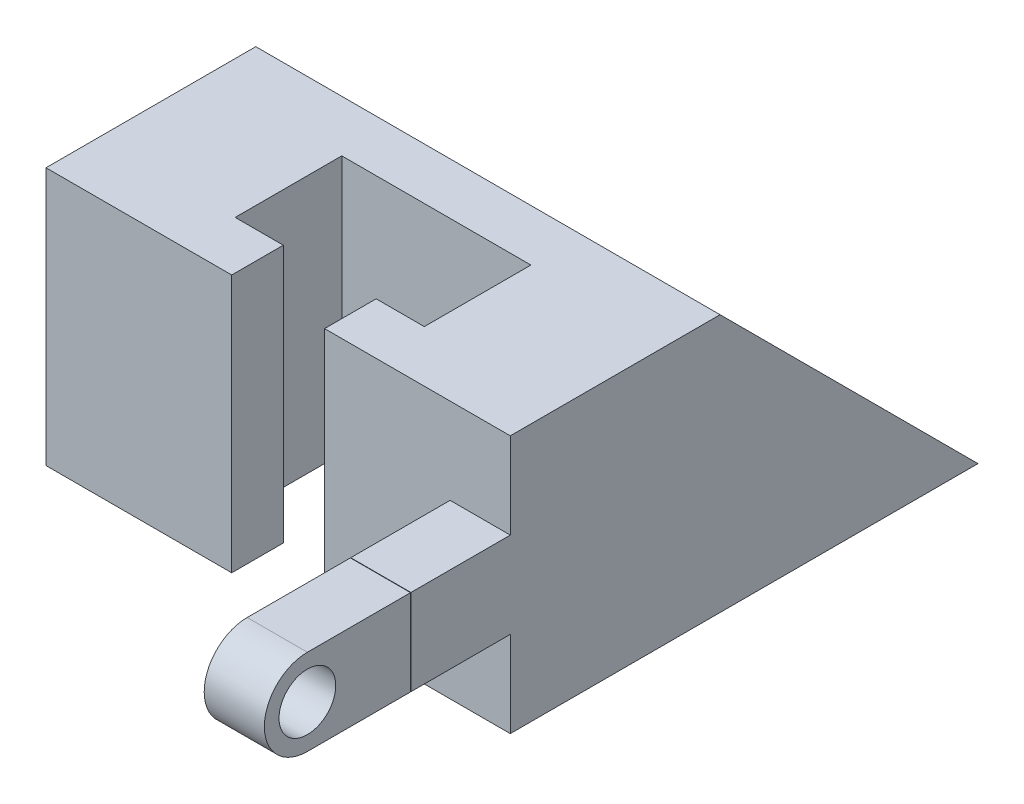
SolidWorks part; units mm, degrees
ref_plane "前视基准面" through (0, 0, 0) normal (0, 0, 1) x (1, 0, 0)
ref_plane "上视基准面" through (0, 0, 0) normal (0, 1, 0) x (1, 0, 0)
ref_plane "右视基准面" through (0, 0, 0) normal (1, 0, 0) x (0, 0, -1)
sketch "草图1" plane through (0, 0, 0) normal (0, 1, 0) x (1, 0, 0)
  line L0 (-5.5, 0) -> (5.5, 0)
  line L1 (5.5, 0) -> (5.5, -6.2)
  line L2 (5.5, -6.2) -> (2.7, -6.2)
  line L3 (2.7, -6.2) -> (2.7, -9.2)
  line L4 (2.7, -9.2) -> (5.5, -9.2)
  line L5 (5.5, -9.2) -> (5.5, -17)
  line L6 (5.5, -17) -> (8.5, -17)
  line L8 (-8.5, 3) -> (8.5, 3)
  line L9 (8.5, 3) -> (8.5, -17)
  line L10 (-5.5, -17) -> (-8.5, -17)
  line L11 (-5.5, -9.2) -> (-5.5, -17)
  line L12 (-2.7, -9.2) -> (-5.5, -9.2)
  line L13 (-2.7, -6.2) -> (-2.7, -9.2)
  line L14 (-5.5, -6.2) -> (-2.7, -6.2)
  line L15 (-5.5, 0) -> (-5.5, -6.2)
  line L16 (-8.5, 3) -> (-8.5, -17)
extrude "凸台-拉伸2" add sketch "草图1" along normal blind 15
sketch "草图2" plane through (8.5, 0, 0) normal (1, 0, 0) x (0, 0, -1)
  line L0 (-17, 15) -> (-17, 10)
  line L1 (-17, 15) -> (-17, 0) construction
  line L2 (-17, 0) -> (-17, 5)
  line L3 (-17, 15) -> (-9.2, 15)
  line L4 (-17, 15) -> (3, 15) construction
  line L5 (-9.2, 15) -> (-9.2, 10)
  line L6 (-9.2, 10) -> (-17, 10)
  line L7 (-17, 5) -> (-9.2, 5)
  line L8 (-9.2, 5) -> (-9.2, 0)
  line L9 (-17, 0) -> (3, 0) construction
  line L10 (-9.2, 0) -> (-17, 0)
extrude "切除-拉伸1" cut sketch "草图2" against normal blind 23
sketch "草图3" plane through (-8.5, 0, 0) normal (-1, 0, 0) x (0, 0, 1)
  line L0 (-3, 15) -> (-3, 7.5)
  line L1 (-3, 15) -> (-3, 0) construction
  line L2 (-3, 7.5) -> (15, 7.5)
  circle A0 centre (15, 7.5) radius 1.65
extrude "切除-拉伸2" cut sketch "草图3" against normal blind 23
sketch "草图4" plane through (0, 0, 17) normal (0, 0, 1) x (1, 0, 0)
  line L0 (-8.5, 10) -> (-5.5, 10)
  line L1 (-8.5, 10) -> (-8.5, 5.005)
  line L2 (-5.5, 10) -> (-5.5, 5.005)
  line L3 (-8.5, 5.005) -> (-5.5, 5.005)
  line L4 (-5.5, 10) -> (-5.5, 5) construction
  line L5 (-8.5, 10) -> (-5.5, 10) construction
  line L6 (5.5, 10) -> (8.5, 10)
  line L7 (5.5, 10) -> (5.5, 4.9814)
  line L8 (8.5, 10) -> (8.5, 4.9814)
  line L9 (5.5, 4.9814) -> (8.5, 4.9814)
extrude "凸台-拉伸3" add sketch "草图4" along normal blind 0.5
sketch "草图5" plane through (-8.5, 0, 0) normal (-1, 0, 0) x (0, 0, 1)
  line L0 (15, 10) -> (17.5, 10)
  line L1 (17.5, 10) -> (17.5, 7.5)
  line L2 (17.5, 7.5) -> (17.5, 5.005)
  line L3 (17.5, 5.005) -> (15, 5)
  line L4 (17.5, 5.005) -> (17.7329, 2.2884)
  line L5 (17.7329, 2.2884) -> (15, 5)
  circle A0 centre (15, 7.5) radius 2.5
extrude "切除-拉伸4" cut sketch "草图5" against normal blind 20.5
sketch "草图7" plane through (-8.5, 0, 0) normal (-1, 0, 0) x (0, 0, 1)
  line L0 (-3, 15) -> (-3, 0)
  line L1 (-3, 0) -> (-18, 0)
  line L2 (-18, 0) -> (-3, 15)
extrude "凸台-拉伸4" add sketch "草图7" against normal blind 17
sketch "草图8" plane through (0, 15, 0) normal (0, 1, 0) x (1, 0, 0)
  line L0 (-8.5, 3) -> (-8.5, 5)
  line L1 (-8.5, 3) -> (-8.5, 18) construction
  line L2 (-8.5, 5) -> (-6.5, 5)
  line L3 (-6.5, 5) -> (-6.5, 18)
  line L4 (-6.5, 5) -> (8.5, 5)
  line L5 (8.5, 3) -> (8.5, 18) construction
  line L6 (8.5, 5) -> (6.5, 5)
  line L7 (6.5, 5) -> (6.5, 18)
  line L8 (6.5, 18) -> (-6.5, 18)
extrude "切除-拉伸5" cut sketch "草图8" against normal blind 14 contours L7 L8 L3 L4
sketch "草图9" plane through (0, 1, 0) normal (0, 1, 0) x (1, 0, 0)
  line L0 (0, 5) -> (0, 8)
  line L1 (-6.5, 5) -> (6.5, 5) construction
  line L2 (0, 8) -> (-4, 8)
  circle A0 centre (-4, 8) radius 1.65
  circle A1 centre (4, 8) radius 1.65
  circle A2 centre (-4, 14) radius 1.65
  circle A3 centre (4, 14) radius 1.65
  dimension "D1" = 2
extrude "切除-拉伸6" cut sketch "草图9" against normal blind 14
sketch "草图10" plane through (-8.5, 0, 0) normal (-1, 0, 0) x (0, 0, 1)
  line L0 (15, 10) -> (25, 10)
  line L2 (15, 5) -> (25, 5)
  line L3 (25, 5) -> (25, 10)
  line L4 (15, 10) -> (15, 5)
  circle A0 centre (25, 7.5) radius 2.5
  circle A1 centre (25, 7.5) radius 1.65
  circle M1 centre (15, 7.5) radius 1.65
  arc M3 (15, 5) -> (15, 10) centre (15, 7.5) ccw
extrude "凸台-拉伸8" add sketch "草图10" along normal mid plane 50 contours A1 L3 A0 | A1 L3 A0 | A0 L0 L2 M3 | L4 M3 M1 | L4 M1 | L4 M1
sketch "草图11" plane through (0, 10, 0) normal (0, 1, 0) x (1, 0, 0)
  line L0 (-8.5, -15) -> (-16.5, -15)
  line L1 (-33.5, -15) -> (-8.5, -15) construction
  line L2 (-8.5, -15) -> (-8.5, -35.0128)
  line L3 (-8.5, -15) -> (-16.7588, -15)
  line L4 (-8.5, -35.0128) -> (-16.7588, -35.0128)
  line L5 (-16.7588, -15) -> (-16.7588, -35.0128)
  line L6 (-16.7588, -35.0128) -> (-38.7573, -35.0128)
  line L7 (-16.7588, -35.0128) -> (-16.7588, 0.8187)
  line L8 (-38.7573, -35.0128) -> (-38.7573, 0.8187)
  line L9 (-16.7588, 0.8187) -> (-38.7573, 0.8187)
  line M3 (-8.5, -15) -> (-33.5, -15)
  line M4 (-33.5, -15) -> (-33.5, -25)
  line M5 (-33.5, -25) -> (16.5, -25)
extrude "切除-拉伸8" cut sketch "草图11" against normal blind 50 contours L7 L9 L8 L6 L5 M5 M4 M3 | L5 M3 M4 M5
sketch "草图13" plane through (8.5, 0, 0) normal (1, 0, 0) x (0, 0, -1)
  line L0 (18, 0) -> (-9.2, 0)
  line L1 (-9.2, 0) -> (-9.2, 5)
  line L2 (-9.2, 5) -> (-15, 5)
  line L3 (-15, 5) -> (-15, 10)
  line L4 (-15, 10) -> (-9.2, 10)
  line L5 (-9.2, 10) -> (-9.2, 15)
  line L6 (-9.2, 15) -> (3, 15)
  line L7 (3, 15) -> (18, 0)
extrude "凸台-拉伸9" add sketch "草图13" along normal blind 8
sketch "草图14" plane through (-8.5, 0, 0) normal (-1, 0, 0) x (0, 0, 1)
  line L0 (15, 10) -> (15, 5)
  line L1 (9.2, 5) -> (15, 5) construction
  line L2 (15, 5) -> (9.2, 5)
  line L3 (9.2, 5) -> (9.2, 0)
  line L4 (9.2, 0) -> (-18, 0)
  line L5 (-18, 0) -> (-3, 15)
  line L6 (-3, 15) -> (9.2, 15)
  line L7 (9.2, 15) -> (9.2, 10)
  line L8 (9.2, 10) -> (15, 10)
extrude "凸台-拉伸11" add sketch "草图14" along normal blind 8
sketch "草图15" plane through (0, 10, 0) normal (0, 1, 0) x (1, 0, 0)
  line L0 (-5.5, -15) -> (-13.5, -15)
  line L1 (-13.5, -15) -> (-13.5, -9.2)
  line L2 (-16.5, -9.2) -> (-5.5, -9.2) construction
  line L3 (5.5, -15) -> (13.5, -15)
  line L4 (13.5, -15) -> (13.5, -9.2)
  line L5 (5.5, -9.2) -> (16.5, -9.2) construction
  line L6 (13.5, -9.2) -> (-13.5, -9.2)
  line L7 (5.5, -15) -> (-5.5, -15)
extrude "切除-拉伸9" cut sketch "草图15" against normal blind 8
sketch "草图16" plane through (0, 0, 15) normal (0, 0, -1) x (-1, 0, 0)
  line L4 (16.7588, 10) -> (16.7588, 5)
  line L5 (16.7588, 10) -> (16.5026, 10)
  line L6 (16.7588, 5) -> (16.5026, 5)
  line L7 (16.5026, 10) -> (16.5026, 5)
extrude "切除-拉伸11" cut sketch "草图16" against normal mid plane 80
sketch "草图17" plane through (0, 10, 0) normal (0, 1, 0) x (1, 0, 0)
  line L0 (13.5, -15) -> (-13.5, -15)
  line L1 (13.5, -15) -> (13.5, -41.9709)
  line L2 (-13.5, -15) -> (-13.5, -41.9709)
  line L3 (13.5, -41.9709) -> (-13.5, -41.9709)
  line L4 (-13.5, -9.2) -> (-13.5, -15) construction
sketch "草图18" plane through (-13.5, 0, 0) normal (1, 0, 0) x (0, 0, -1)
  line L0 (-9.2, 5) -> (-9.2, 10)
  line L1 (-9.2, 5) -> (-14.9767, 5)
  line L2 (-9.2, 10) -> (-14.9767, 10)
  line L3 (-14.9767, 5) -> (-14.9767, 10)
extrude "凸台-拉伸13" add sketch "草图18" along normal blind 29
sketch "草图19" plane through (0, 5, 0) normal (0, -1, 0) x (1, 0, 0)
  line L0 (0, 9.2) -> (-10, 9.2)
  line L1 (2.7, 9.2) -> (-2.7, 9.2) construction
  line L2 (-16.5, 9.2) -> (-2.7, 9.2) construction
  line L3 (0, 9.2) -> (10, 9.2)
  line L4 (2.7, 9.2) -> (16.5, 9.2) construction
  line L5 (10, 9.2) -> (10, 29.3376)
  line L7 (-10, 29.3376) -> (10, 29.3376)
  line L8 (-10, 29.3376) -> (-10, 9.2)
extrude "切除-拉伸13" cut sketch "草图19" against normal blind 24
sketch "草图20" plane through (0, 0, 0) normal (0, -1, 0) x (1, 0, 0)
  line L0 (-16.5, 9.2) -> (-13.5, 9.2)
  line L1 (-16.5, 9.2) -> (-2.7, 9.2) construction
  line L2 (16.5, 9.2) -> (13.5, 9.2)
  line L3 (2.7, 9.2) -> (16.5, 9.2) construction
  line L4 (13.5, 9.2) -> (13.5, -18)
  line L5 (16.5, -18) -> (-16.5, -18) construction
  line L6 (13.5, -18) -> (16.5, -18)
  line L7 (16.5, -18) -> (16.5, 42.2455)
  line L8 (16.5, 42.2455) -> (13.5, 42.2455)
  line L9 (13.5, 42.2455) -> (13.5, 9.2)
  line L10 (-13.5, 9.2) -> (-13.5, 43.5506)
  line L11 (-13.5, 43.5506) -> (-16.5, 43.5506)
  line L12 (-16.5, 43.5506) -> (-16.5, -18)
  line L13 (-16.5, -18) -> (-16.5, 9.2) construction
  line L14 (-16.5, -18) -> (-13.5, -18)
  line L15 (-13.5, -18) -> (-13.5, 9.2)
  line L16 (16.5, 42.2455) -> (39.5508, 38.5955)
  line L17 (39.5508, 38.5955) -> (42.4056, -22.5054)
  line L18 (42.4056, -22.5054) -> (16.5, -18)
  line L19 (-16.5, 43.5506) -> (-30.1917, 43.5506)
  line L20 (-30.1917, 43.5506) -> (-32.6273, -13.9343)
  line L21 (-32.6273, -13.9343) -> (-16.5, -18)
  line M4 (-2.7, 9.2) -> (-16.5, 9.2)
  line M5 (-16.5, 9.2) -> (-16.5, -18)
  line M6 (-16.5, -18) -> (16.5, -18)
  line M7 (16.5, -18) -> (16.5, 9.2)
  line M8 (16.5, 9.2) -> (2.7, 9.2)
extrude "切除-拉伸16" cut sketch "草图20" against normal through all contours L18 L17 L16 L7 M7 | L8 L9 L7 M8 | L4 M8 M6 M7 | L11 L12 L10 M4 | L15 M6 M4 M5 | L20 L21 L12 L19 M5
sketch "草图21" plane through (0, 5, 0) normal (0, -1, 0) x (1, 0, 0)
  line L0 (-13.5, 9.2) -> (-10, 9.2)
  line L1 (-13.5, 9.2) -> (-13.5, 28.5646)
  line L2 (-10, 9.2) -> (-10, 28.5646)
  line L3 (-13.5, 28.5646) -> (-10, 28.5646)
extrude "切除-拉伸17" cut sketch "草图21" against normal blind 10
sketch "草图22" plane through (13.5, 0, 0) normal (1, 0, 0) x (0, 0, -1)
  circle A0 centre (-25, 7.5) radius 1.65
extrude "凸台-拉伸14" add sketch "草图22" against normal blind 3.5
sketch "草图23" plane through (13.5, 0, 0) normal (1, 0, 0) x (0, 0, -1)
  line L0 (-9.2, 5) -> (-9.2, 10)
  line L1 (-9.2, 10) -> (-9.2, 7.5)
  line L2 (-9.2, 7.5) -> (-21, 7.5)
  line L3 (-21, 5) -> (-28.428, 0)
  line L4 (-28.428, 0) -> (-29.4139, 12.6342)
  line L5 (-29.4139, 12.6342) -> (-21, 10)
  circle A0 centre (-21, 7.5) radius 1.65
  circle A1 centre (-21, 7.5) radius 2.5
extrude "切除-拉伸18" cut sketch "草图23" against normal blind 3.5
